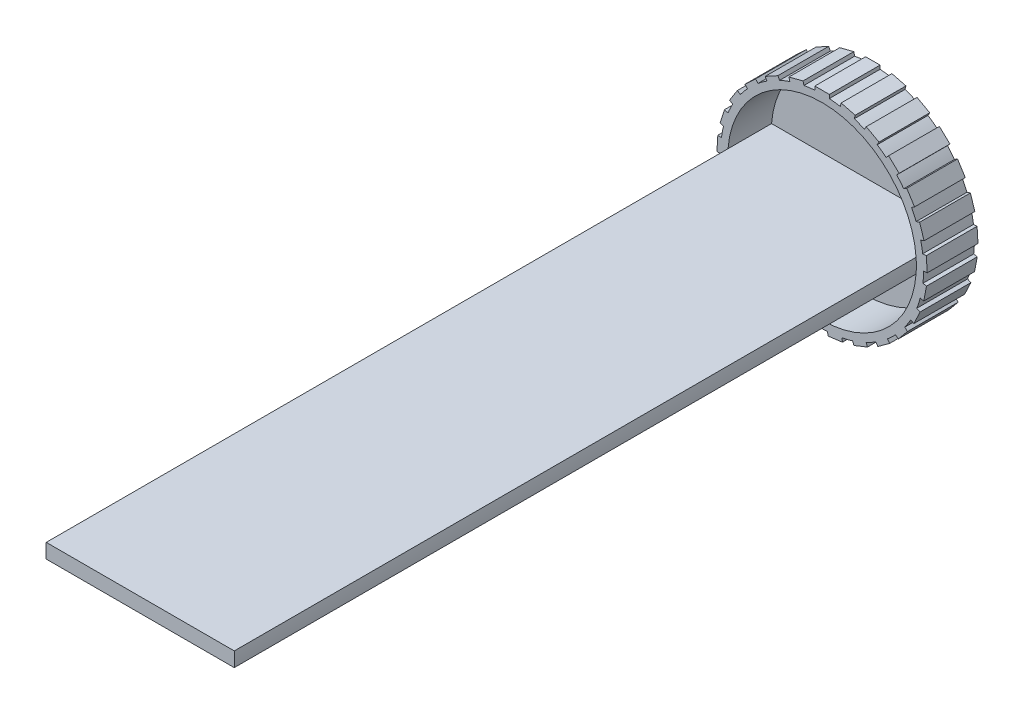
SolidWorks part; units mm, degrees
ref_plane "Ön Düzlem" through (0, 0, 0) normal (0, 0, 1) x (1, 0, 0)
ref_plane "Üst Düzlem" through (0, 0, 0) normal (0, 1, 0) x (1, 0, 0)
ref_plane "Sağ Düzlem" through (0, 0, 0) normal (1, 0, 0) x (0, 0, -1)
sketch "Çizim1" plane through (0, 0, 0) normal (0, 0, 1) x (1, 0, 0)
  line L0 (17.9856, 70.0491) -> (13.1426, 71.2925)
  line L1 (0, 72.3212) -> (-5, 72.3212)
  line L2 (-5, 72.3212) -> (-5, 69.8212)
  line L3 (0, 72.3212) -> (5, 72.3212)
  line L4 (5, 72.3212) -> (5, 69.8212)
  line L5 (13.1426, 71.2925) -> (12.5209, 68.8711)
  line L6 (17.9856, 70.0491) -> (22.8285, 68.8056)
  line L7 (22.8285, 68.8056) -> (22.2067, 66.3842)
  line L8 (34.841, 63.3756) -> (30.4595, 65.7843)
  line L9 (30.4595, 65.7843) -> (29.2551, 63.5936)
  line L10 (34.841, 63.3756) -> (39.2225, 60.9668)
  line L11 (39.2225, 60.9668) -> (38.0182, 58.776)
  line L12 (49.5073, 52.7199) -> (45.8624, 56.1426)
  line L13 (45.8624, 56.1426) -> (44.1511, 54.3202)
  line L14 (49.5073, 52.7199) -> (53.1521, 49.2972)
  line L15 (53.1521, 49.2972) -> (51.4407, 47.4747)
  line L16 (61.0628, 38.7516) -> (58.3837, 42.9733)
  line L17 (58.3837, 42.9733) -> (56.2729, 41.6337)
  line L18 (61.0628, 38.7516) -> (63.7419, 34.53)
  line L19 (63.7419, 34.53) -> (61.6311, 33.1904)
  line L20 (68.7815, 22.3485) -> (67.2365, 27.1038)
  line L21 (67.2365, 27.1038) -> (64.8588, 26.3312)
  line L22 (68.7815, 22.3485) -> (70.3266, 17.5932)
  line L23 (70.3266, 17.5932) -> (67.949, 16.8207)
  line L24 (72.1785, 4.5411) -> (71.8645, 9.5312)
  line L25 (71.8645, 9.5312) -> (69.3695, 9.3742)
  line L26 (72.1785, 4.5411) -> (72.4924, -0.449)
  line L27 (72.4924, -0.449) -> (69.9974, -0.606)
  line L28 (71.0402, -13.5516) -> (71.9771, -8.6402)
  line L29 (71.9771, -8.6402) -> (69.5214, -8.1718)
  line L30 (71.0402, -13.5516) -> (70.1033, -18.4631)
  line L31 (70.1033, -18.4631) -> (67.6476, -17.9946)
  line L32 (65.4382, -30.7929) -> (67.5671, -26.2687)
  line L33 (67.5671, -26.2687) -> (65.305, -25.2043)
  line L34 (65.4382, -30.7929) -> (63.3093, -35.317)
  line L35 (63.3093, -35.317) -> (61.0472, -34.2526)
  line L36 (55.7244, -46.0993) -> (58.9116, -42.2467)
  line L37 (58.9116, -42.2467) -> (56.9853, -40.6531)
  line L38 (55.7244, -46.0993) -> (52.5373, -49.9518)
  line L39 (52.5373, -49.9518) -> (50.611, -48.3583)
  line L40 (42.5093, -58.5091) -> (46.5544, -55.5702)
  line L41 (46.5544, -55.5702) -> (45.085, -53.5476)
  line L42 (42.5093, -58.5091) -> (38.4642, -61.448)
  line L43 (38.4642, -61.448) -> (36.9948, -59.4255)
  line L44 (26.6232, -67.2426) -> (31.2721, -65.4019)
  line L45 (31.2721, -65.4019) -> (30.3518, -63.0775)
  line L46 (26.6232, -67.2426) -> (21.9743, -69.0832)
  line L47 (21.9743, -69.0832) -> (21.054, -66.7587)
  line L48 (9.0642, -71.7509) -> (14.0248, -71.1243)
  line L49 (14.0248, -71.1243) -> (13.7115, -68.644)
  line L50 (9.0642, -71.7509) -> (4.1037, -72.3776)
  line L51 (4.1037, -72.3776) -> (3.7903, -69.8973)
  line L52 (-9.0642, -71.7509) -> (-4.1037, -72.3776)
  line L53 (-4.1037, -72.3776) -> (-3.7903, -69.8973)
  line L54 (-9.0642, -71.7509) -> (-14.0248, -71.1243)
  line L55 (-14.0248, -71.1243) -> (-13.7115, -68.644)
  line L56 (-26.6232, -67.2426) -> (-21.9743, -69.0832)
  line L57 (-21.9743, -69.0832) -> (-21.054, -66.7587)
  line L58 (-26.6232, -67.2426) -> (-31.2721, -65.4019)
  line L59 (-31.2721, -65.4019) -> (-30.3518, -63.0775)
  line L60 (-42.5093, -58.5091) -> (-38.4642, -61.448)
  line L61 (-38.4642, -61.448) -> (-36.9948, -59.4255)
  line L62 (-42.5093, -58.5091) -> (-46.5544, -55.5702)
  line L63 (-46.5544, -55.5702) -> (-45.085, -53.5476)
  line L64 (-55.7244, -46.0993) -> (-52.5373, -49.9518)
  line L65 (-52.5373, -49.9518) -> (-50.611, -48.3583)
  line L66 (-55.7244, -46.0993) -> (-58.9116, -42.2467)
  line L67 (-58.9116, -42.2467) -> (-56.9853, -40.6531)
  line L68 (-65.4382, -30.7929) -> (-63.3093, -35.317)
  line L69 (-63.3093, -35.317) -> (-61.0472, -34.2526)
  line L70 (-65.4382, -30.7929) -> (-67.5671, -26.2687)
  line L71 (-67.5671, -26.2687) -> (-65.305, -25.2043)
  line L72 (-71.0402, -13.5516) -> (-70.1033, -18.4631)
  line L73 (-70.1033, -18.4631) -> (-67.6476, -17.9946)
  line L74 (-71.0402, -13.5516) -> (-71.9771, -8.6402)
  line L75 (-71.9771, -8.6402) -> (-69.5214, -8.1718)
  line L76 (-72.1785, 4.5411) -> (-72.4924, -0.449)
  line L77 (-72.4924, -0.449) -> (-69.9974, -0.606)
  line L78 (-72.1785, 4.5411) -> (-71.8645, 9.5312)
  line L79 (-71.8645, 9.5312) -> (-69.3695, 9.3742)
  line L80 (-68.7815, 22.3485) -> (-70.3266, 17.5932)
  line L81 (-70.3266, 17.5932) -> (-67.949, 16.8207)
  line L82 (-68.7815, 22.3485) -> (-67.2365, 27.1038)
  line L83 (-67.2365, 27.1038) -> (-64.8588, 26.3312)
  line L84 (-61.0628, 38.7516) -> (-63.7419, 34.53)
  line L85 (-63.7419, 34.53) -> (-61.6311, 33.1904)
  line L86 (-61.0628, 38.7516) -> (-58.3837, 42.9733)
  line L87 (-58.3837, 42.9733) -> (-56.2729, 41.6337)
  line L88 (-49.5073, 52.7199) -> (-53.1521, 49.2972)
  line L89 (-53.1521, 49.2972) -> (-51.4407, 47.4747)
  line L90 (-49.5073, 52.7199) -> (-45.8624, 56.1426)
  line L91 (-45.8624, 56.1426) -> (-44.1511, 54.3202)
  line L92 (-34.841, 63.3756) -> (-39.2225, 60.9668)
  line L93 (-39.2225, 60.9668) -> (-38.0182, 58.776)
  line L94 (-34.841, 63.3756) -> (-30.4595, 65.7843)
  line L95 (-30.4595, 65.7843) -> (-29.2551, 63.5936)
  line L96 (-17.9856, 70.0491) -> (-22.8285, 68.8056)
  line L97 (-22.8285, 68.8056) -> (-22.2067, 66.3842)
  line L98 (-17.9856, 70.0491) -> (-13.1426, 71.2925)
  line L99 (-13.1426, 71.2925) -> (-12.5209, 68.8711)
  arc A0 (-61.6311, 33.1904) -> (-64.8588, 26.3312) centre (0, 0) ccw construction
  arc A1 (-51.4407, 47.4747) -> (-56.2729, 41.6337) centre (0, 0) ccw
  arc A2 (-51.4407, 47.4747) -> (-56.2729, 41.6337) centre (0, 0) ccw construction
  arc A3 (-38.0182, 58.776) -> (-44.1511, 54.3202) centre (0, 0) ccw construction
  arc A4 (-38.0182, 58.776) -> (-44.1511, 54.3202) centre (0, 0) ccw
  arc A5 (-22.2067, 66.3842) -> (-29.2551, 63.5936) centre (0, 0) ccw construction
  arc A6 (-5, 69.8212) -> (-12.5209, 68.8711) centre (0, 0) ccw
  arc A7 (-5, 69.8212) -> (-12.5209, 68.8711) centre (0, 0) ccw construction
  arc A8 (12.5209, 68.8711) -> (5, 69.8212) centre (0, 0) ccw construction
  arc A9 (12.5209, 68.8711) -> (5, 69.8212) centre (0, 0) ccw
  arc A10 (29.2551, 63.5936) -> (22.2067, 66.3842) centre (0, 0) ccw construction
  arc A11 (29.2551, 63.5936) -> (22.2067, 66.3842) centre (0, 0) ccw
  arc A12 (44.1511, 54.3202) -> (38.0182, 58.776) centre (0, 0) ccw construction
  arc A13 (44.1511, 54.3202) -> (38.0182, 58.776) centre (0, 0) ccw
  arc A14 (56.2729, 41.6337) -> (51.4407, 47.4747) centre (0, 0) ccw construction
  arc A15 (56.2729, 41.6337) -> (51.4407, 47.4747) centre (0, 0) ccw
  arc A16 (64.8588, 26.3312) -> (61.6311, 33.1904) centre (0, 0) ccw construction
  arc A17 (64.8588, 26.3312) -> (61.6311, 33.1904) centre (0, 0) ccw
  arc A18 (-22.2067, 66.3842) -> (-29.2551, 63.5936) centre (0, 0) ccw
  arc A19 (-61.6311, 33.1904) -> (-64.8588, 26.3312) centre (0, 0) ccw
  arc A20 (-67.949, 16.8207) -> (-69.3695, 9.3742) centre (0, 0) ccw construction
  arc A21 (-67.949, 16.8207) -> (-69.3695, 9.3742) centre (0, 0) ccw
  arc A22 (-69.9974, -0.606) -> (-69.5214, -8.1718) centre (0, 0) ccw construction
  arc A23 (-69.9974, -0.606) -> (-69.5214, -8.1718) centre (0, 0) ccw
  arc A24 (-67.6476, -17.9946) -> (-65.305, -25.2043) centre (0, 0) ccw construction
  arc A25 (-67.6476, -17.9946) -> (-65.305, -25.2043) centre (0, 0) ccw
  arc A26 (-61.0472, -34.2526) -> (-56.9853, -40.6531) centre (0, 0) ccw construction
  arc A27 (-61.0472, -34.2526) -> (-56.9853, -40.6531) centre (0, 0) ccw
  arc A28 (-50.611, -48.3583) -> (-45.085, -53.5476) centre (0, 0) ccw construction
  arc A29 (-50.611, -48.3583) -> (-45.085, -53.5476) centre (0, 0) ccw
  arc A30 (-36.9948, -59.4255) -> (-30.3518, -63.0775) centre (0, 0) ccw construction
  arc A31 (-36.9948, -59.4255) -> (-30.3518, -63.0775) centre (0, 0) ccw
  arc A32 (-21.054, -66.7587) -> (-13.7115, -68.644) centre (0, 0) ccw construction
  arc A33 (-21.054, -66.7587) -> (-13.7115, -68.644) centre (0, 0) ccw
  arc A34 (-3.7903, -69.8973) -> (3.7903, -69.8973) centre (0, 0) ccw construction
  arc A35 (-3.7903, -69.8973) -> (3.7903, -69.8973) centre (0, 0) ccw
  arc A36 (13.7115, -68.644) -> (21.054, -66.7587) centre (0, 0) ccw construction
  arc A37 (13.7115, -68.644) -> (21.054, -66.7587) centre (0, 0) ccw
  arc A38 (30.3518, -63.0775) -> (36.9948, -59.4255) centre (0, 0) ccw construction
  arc A39 (30.3518, -63.0775) -> (36.9948, -59.4255) centre (0, 0) ccw
  arc A40 (45.085, -53.5476) -> (50.611, -48.3583) centre (0, 0) ccw construction
  arc A41 (45.085, -53.5476) -> (50.611, -48.3583) centre (0, 0) ccw
  arc A42 (56.9853, -40.6531) -> (61.0472, -34.2526) centre (0, 0) ccw construction
  arc A43 (56.9853, -40.6531) -> (61.0472, -34.2526) centre (0, 0) ccw
  arc A44 (65.305, -25.2043) -> (67.6476, -17.9946) centre (0, 0) ccw construction
  arc A45 (65.305, -25.2043) -> (67.6476, -17.9946) centre (0, 0) ccw
  arc A46 (69.5214, -8.1718) -> (69.9974, -0.606) centre (0, 0) ccw construction
  arc A47 (69.5214, -8.1718) -> (69.9974, -0.606) centre (0, 0) ccw
  arc A48 (69.3695, 9.3742) -> (67.949, 16.8207) centre (0, 0) ccw construction
  arc A49 (69.3695, 9.3742) -> (67.949, 16.8207) centre (0, 0) ccw
  circle A50 centre (0, 0) radius 65
  point P130 (0, 0)
  dimension "D1" = 140
  dimension "D2" = 5
  dimension "D6" = 130
  dimension "D3" = 5
  dimension "D4" = 2.5
  dimension "D5" = 25
extrude "Yükseklik-Ekstrüzyon1" add sketch "Çizim1" along normal blind 30
sketch "Çizim2" plane through (0, 0, 0) normal (0, 0, -1) x (-1, 0, 0)
  line L0 (17.9856, 70.0491) -> (13.1426, 71.2925)
  line L1 (0, 72.3212) -> (-5, 72.3212)
  line L2 (-5, 72.3212) -> (-5, 69.8212)
  line L3 (0, 72.3212) -> (5, 72.3212)
  line L4 (5, 72.3212) -> (5, 69.8212)
  line L5 (13.1426, 71.2925) -> (12.5209, 68.8711)
  line L6 (17.9856, 70.0491) -> (22.8285, 68.8056)
  line L7 (22.8285, 68.8056) -> (22.2067, 66.3842)
  line L8 (34.841, 63.3756) -> (30.4595, 65.7843)
  line L9 (30.4595, 65.7843) -> (29.2551, 63.5936)
  line L10 (34.841, 63.3756) -> (39.2225, 60.9668)
  line L11 (39.2225, 60.9668) -> (38.0182, 58.776)
  line L12 (49.5073, 52.7199) -> (45.8624, 56.1426)
  line L13 (45.8624, 56.1426) -> (44.1511, 54.3202)
  line L14 (49.5073, 52.7199) -> (53.1521, 49.2972)
  line L15 (53.1521, 49.2972) -> (51.4407, 47.4747)
  line L16 (61.0628, 38.7516) -> (58.3837, 42.9733)
  line L17 (58.3837, 42.9733) -> (56.2729, 41.6337)
  line L18 (61.0628, 38.7516) -> (63.7419, 34.53)
  line L19 (63.7419, 34.53) -> (61.6311, 33.1904)
  line L20 (68.7815, 22.3485) -> (67.2365, 27.1038)
  line L21 (67.2365, 27.1038) -> (64.8588, 26.3312)
  line L22 (68.7815, 22.3485) -> (70.3266, 17.5932)
  line L23 (70.3266, 17.5932) -> (67.949, 16.8207)
  line L24 (72.1785, 4.5411) -> (71.8645, 9.5312)
  line L25 (71.8645, 9.5312) -> (69.3695, 9.3742)
  line L26 (72.1785, 4.5411) -> (72.4924, -0.449)
  line L27 (72.4924, -0.449) -> (69.9974, -0.606)
  line L28 (71.0402, -13.5516) -> (71.9771, -8.6402)
  line L29 (71.9771, -8.6402) -> (69.5214, -8.1718)
  line L30 (71.0402, -13.5516) -> (70.1033, -18.4631)
  line L31 (70.1033, -18.4631) -> (67.6476, -17.9946)
  line L32 (65.4382, -30.7929) -> (67.5671, -26.2687)
  line L33 (67.5671, -26.2687) -> (65.305, -25.2043)
  line L34 (65.4382, -30.7929) -> (63.3093, -35.317)
  line L35 (63.3093, -35.317) -> (61.0472, -34.2526)
  line L36 (55.7244, -46.0993) -> (58.9116, -42.2467)
  line L37 (58.9116, -42.2467) -> (56.9853, -40.6531)
  line L38 (55.7244, -46.0993) -> (52.5373, -49.9518)
  line L39 (52.5373, -49.9518) -> (50.611, -48.3583)
  line L40 (42.5093, -58.5091) -> (46.5544, -55.5702)
  line L41 (46.5544, -55.5702) -> (45.085, -53.5476)
  line L42 (42.5093, -58.5091) -> (38.4642, -61.448)
  line L43 (38.4642, -61.448) -> (36.9948, -59.4255)
  line L44 (26.6232, -67.2426) -> (31.2721, -65.4019)
  line L45 (31.2721, -65.4019) -> (30.3518, -63.0775)
  line L46 (26.6232, -67.2426) -> (21.9743, -69.0832)
  line L47 (21.9743, -69.0832) -> (21.054, -66.7587)
  line L48 (9.0642, -71.7509) -> (14.0248, -71.1243)
  line L49 (14.0248, -71.1243) -> (13.7115, -68.644)
  line L50 (9.0642, -71.7509) -> (4.1037, -72.3776)
  line L51 (4.1037, -72.3776) -> (3.7903, -69.8973)
  line L52 (-9.0642, -71.7509) -> (-4.1037, -72.3776)
  line L53 (-4.1037, -72.3776) -> (-3.7903, -69.8973)
  line L54 (-9.0642, -71.7509) -> (-14.0248, -71.1243)
  line L55 (-14.0248, -71.1243) -> (-13.7115, -68.644)
  line L56 (-26.6232, -67.2426) -> (-21.9743, -69.0832)
  line L57 (-21.9743, -69.0832) -> (-21.054, -66.7587)
  line L58 (-26.6232, -67.2426) -> (-31.2721, -65.4019)
  line L59 (-31.2721, -65.4019) -> (-30.3518, -63.0775)
  line L60 (-42.5093, -58.5091) -> (-38.4642, -61.448)
  line L61 (-38.4642, -61.448) -> (-36.9948, -59.4255)
  line L62 (-42.5093, -58.5091) -> (-46.5544, -55.5702)
  line L63 (-46.5544, -55.5702) -> (-45.085, -53.5476)
  line L64 (-55.7244, -46.0993) -> (-52.5373, -49.9518)
  line L65 (-52.5373, -49.9518) -> (-50.611, -48.3583)
  line L66 (-55.7244, -46.0993) -> (-58.9116, -42.2467)
  line L67 (-58.9116, -42.2467) -> (-56.9853, -40.6531)
  line L68 (-65.4382, -30.7929) -> (-63.3093, -35.317)
  line L69 (-63.3093, -35.317) -> (-61.0472, -34.2526)
  line L70 (-65.4382, -30.7929) -> (-67.5671, -26.2687)
  line L71 (-67.5671, -26.2687) -> (-65.305, -25.2043)
  line L72 (-71.0402, -13.5516) -> (-70.1033, -18.4631)
  line L73 (-70.1033, -18.4631) -> (-67.6476, -17.9946)
  line L74 (-71.0402, -13.5516) -> (-71.9771, -8.6402)
  line L75 (-71.9771, -8.6402) -> (-69.5214, -8.1718)
  line L76 (-72.1785, 4.5411) -> (-72.4924, -0.449)
  line L77 (-72.4924, -0.449) -> (-69.9974, -0.606)
  line L78 (-72.1785, 4.5411) -> (-71.8645, 9.5312)
  line L79 (-71.8645, 9.5312) -> (-69.3695, 9.3742)
  line L80 (-68.7815, 22.3485) -> (-70.3266, 17.5932)
  line L81 (-70.3266, 17.5932) -> (-67.949, 16.8207)
  line L82 (-68.7815, 22.3485) -> (-67.2365, 27.1038)
  line L83 (-67.2365, 27.1038) -> (-64.8588, 26.3312)
  line L84 (-61.0628, 38.7516) -> (-63.7419, 34.53)
  line L85 (-63.7419, 34.53) -> (-61.6311, 33.1904)
  line L86 (-61.0628, 38.7516) -> (-58.3837, 42.9733)
  line L87 (-58.3837, 42.9733) -> (-56.2729, 41.6337)
  line L88 (-49.5073, 52.7199) -> (-53.1521, 49.2972)
  line L89 (-53.1521, 49.2972) -> (-51.4407, 47.4747)
  line L90 (-49.5073, 52.7199) -> (-45.8624, 56.1426)
  line L91 (-45.8624, 56.1426) -> (-44.1511, 54.3202)
  line L92 (-34.841, 63.3756) -> (-39.2225, 60.9668)
  line L93 (-39.2225, 60.9668) -> (-38.0182, 58.776)
  line L94 (-34.841, 63.3756) -> (-30.4595, 65.7843)
  line L95 (-30.4595, 65.7843) -> (-29.2551, 63.5936)
  line L96 (-17.9856, 70.0491) -> (-22.8285, 68.8056)
  line L97 (-22.8285, 68.8056) -> (-22.2067, 66.3842)
  line L98 (-17.9856, 70.0491) -> (-13.1426, 71.2925)
  line L99 (-13.1426, 71.2925) -> (-12.5209, 68.8711)
  arc A0 (-61.6311, 33.1904) -> (-64.8588, 26.3312) centre (0, 0) ccw construction
  arc A1 (-51.4407, 47.4747) -> (-56.2729, 41.6337) centre (0, 0) ccw
  arc A2 (-51.4407, 47.4747) -> (-56.2729, 41.6337) centre (0, 0) ccw construction
  arc A3 (-38.0182, 58.776) -> (-44.1511, 54.3202) centre (0, 0) ccw construction
  arc A4 (-38.0182, 58.776) -> (-44.1511, 54.3202) centre (0, 0) ccw
  arc A5 (-22.2067, 66.3842) -> (-29.2551, 63.5936) centre (0, 0) ccw construction
  arc A6 (-5, 69.8212) -> (-12.5209, 68.8711) centre (0, 0) ccw
  arc A7 (-5, 69.8212) -> (-12.5209, 68.8711) centre (0, 0) ccw construction
  arc A8 (12.5209, 68.8711) -> (5, 69.8212) centre (0, 0) ccw construction
  arc A9 (12.5209, 68.8711) -> (5, 69.8212) centre (0, 0) ccw
  arc A10 (29.2551, 63.5936) -> (22.2067, 66.3842) centre (0, 0) ccw construction
  arc A11 (29.2551, 63.5936) -> (22.2067, 66.3842) centre (0, 0) ccw
  arc A12 (44.1511, 54.3202) -> (38.0182, 58.776) centre (0, 0) ccw construction
  arc A13 (44.1511, 54.3202) -> (38.0182, 58.776) centre (0, 0) ccw
  arc A14 (56.2729, 41.6337) -> (51.4407, 47.4747) centre (0, 0) ccw construction
  arc A15 (56.2729, 41.6337) -> (51.4407, 47.4747) centre (0, 0) ccw
  arc A16 (64.8588, 26.3312) -> (61.6311, 33.1904) centre (0, 0) ccw construction
  arc A17 (64.8588, 26.3312) -> (61.6311, 33.1904) centre (0, 0) ccw
  arc A18 (-22.2067, 66.3842) -> (-29.2551, 63.5936) centre (0, 0) ccw
  arc A19 (-61.6311, 33.1904) -> (-64.8588, 26.3312) centre (0, 0) ccw
  arc A20 (-67.949, 16.8207) -> (-69.3695, 9.3742) centre (0, 0) ccw construction
  arc A21 (-67.949, 16.8207) -> (-69.3695, 9.3742) centre (0, 0) ccw
  arc A22 (-69.9974, -0.606) -> (-69.5214, -8.1718) centre (0, 0) ccw construction
  arc A23 (-69.9974, -0.606) -> (-69.5214, -8.1718) centre (0, 0) ccw
  arc A24 (-67.6476, -17.9946) -> (-65.305, -25.2043) centre (0, 0) ccw construction
  arc A25 (-67.6476, -17.9946) -> (-65.305, -25.2043) centre (0, 0) ccw
  arc A26 (-61.0472, -34.2526) -> (-56.9853, -40.6531) centre (0, 0) ccw construction
  arc A27 (-61.0472, -34.2526) -> (-56.9853, -40.6531) centre (0, 0) ccw
  arc A28 (-50.611, -48.3583) -> (-45.085, -53.5476) centre (0, 0) ccw construction
  arc A29 (-50.611, -48.3583) -> (-45.085, -53.5476) centre (0, 0) ccw
  arc A30 (-36.9948, -59.4255) -> (-30.3518, -63.0775) centre (0, 0) ccw construction
  arc A31 (-36.9948, -59.4255) -> (-30.3518, -63.0775) centre (0, 0) ccw
  arc A32 (-21.054, -66.7587) -> (-13.7115, -68.644) centre (0, 0) ccw construction
  arc A33 (-21.054, -66.7587) -> (-13.7115, -68.644) centre (0, 0) ccw
  arc A34 (-3.7903, -69.8973) -> (3.7903, -69.8973) centre (0, 0) ccw construction
  arc A35 (-3.7903, -69.8973) -> (3.7903, -69.8973) centre (0, 0) ccw
  arc A36 (13.7115, -68.644) -> (21.054, -66.7587) centre (0, 0) ccw construction
  arc A37 (13.7115, -68.644) -> (21.054, -66.7587) centre (0, 0) ccw
  arc A38 (30.3518, -63.0775) -> (36.9948, -59.4255) centre (0, 0) ccw construction
  arc A39 (30.3518, -63.0775) -> (36.9948, -59.4255) centre (0, 0) ccw
  arc A40 (45.085, -53.5476) -> (50.611, -48.3583) centre (0, 0) ccw construction
  arc A41 (45.085, -53.5476) -> (50.611, -48.3583) centre (0, 0) ccw
  arc A42 (56.9853, -40.6531) -> (61.0472, -34.2526) centre (0, 0) ccw construction
  arc A43 (56.9853, -40.6531) -> (61.0472, -34.2526) centre (0, 0) ccw
  arc A44 (65.305, -25.2043) -> (67.6476, -17.9946) centre (0, 0) ccw construction
  arc A45 (65.305, -25.2043) -> (67.6476, -17.9946) centre (0, 0) ccw
  arc A46 (69.5214, -8.1718) -> (69.9974, -0.606) centre (0, 0) ccw construction
  arc A47 (69.5214, -8.1718) -> (69.9974, -0.606) centre (0, 0) ccw
  arc A48 (69.3695, 9.3742) -> (67.949, 16.8207) centre (0, 0) ccw construction
  arc A49 (69.3695, 9.3742) -> (67.949, 16.8207) centre (0, 0) ccw
  point P127 (-1.1942, -11.3247)
extrude "Yükseklik-Ekstrüzyon3" add sketch "Çizim2" along normal blind 5
sketch "Çizim3" plane through (0, 0, 0) normal (0, 0, 1) x (1, 0, 0)
  line L1 (-64.8074, 5) -> (64.8074, 5)
  line L3 (-64.8074, -5) -> (64.8074, -5)
  line L5 (-64.8197, 4.8381) -> (64.8197, -4.8381) construction
  line L6 (-64.8197, -4.8381) -> (64.8197, 4.8381) construction
  arc A0 (-64.8074, 5) -> (-64.8074, -5) centre (0, 0) ccw
  arc A1 (64.8074, -5) -> (64.8074, 5) centre (0, 0) ccw
  dimension "D1" = 10
extrude "Yükseklik-Ekstrüzyon4" add sketch "Çizim3" along normal blind 500
